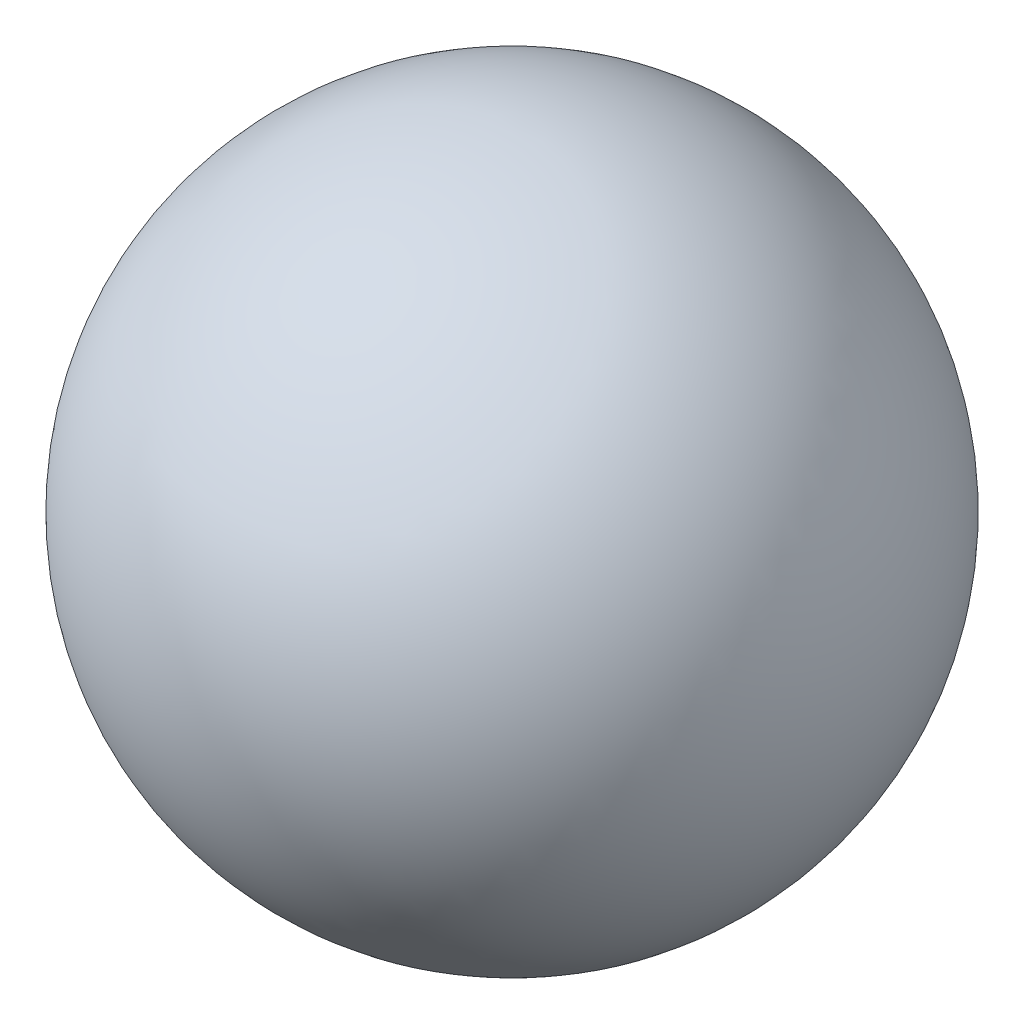
SolidWorks part; units mm, degrees
ref_plane "正面" through (0, 0, 0) normal (0, 0, 1) x (1, 0, 0)
ref_plane "平面" through (0, 0, 0) normal (0, 1, 0) x (1, 0, 0)
ref_plane "右側面" through (0, 0, 0) normal (1, 0, 0) x (0, 0, -1)
sketch "ｽｹｯﾁ1" plane through (0, 0, 0) normal (0, 0, 1) x (1, 0, 0)
  line L0 (0, 70) -> (0, -70)
  arc A0 (0, 70) -> (0, -70) centre (0, 0) cw
  dimension "D1" = 70
revolve "回転1" add sketch "ｽｹｯﾁ1" angle 360 about L0
